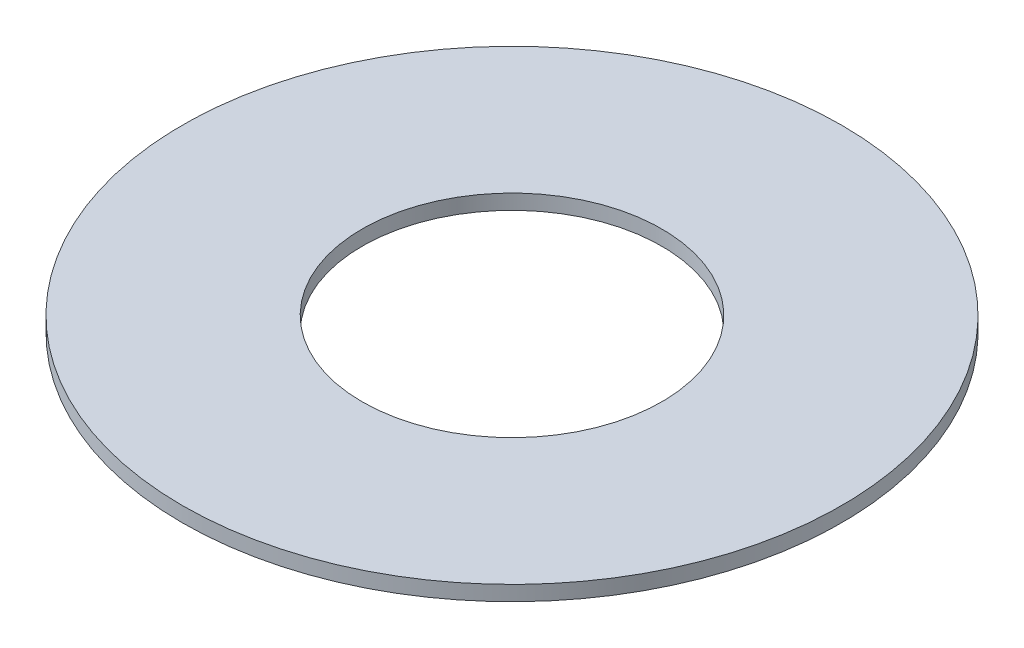
SolidWorks part; units mm, degrees
material "ПТФЭ (общий)"
ref_plane "Спереди" through (0, 0, 0) normal (0, 0, 1) x (1, 0, 0)
ref_plane "Сверху" through (0, 0, 0) normal (0, 1, 0) x (1, 0, 0)
ref_plane "Справа" through (0, 0, 0) normal (1, 0, 0) x (0, 0, -1)
sketch "Эскиз1" plane through (0, 0, 0) normal (0, 1, 0) x (1, 0, 0)
  circle A0 centre (0, 0) radius 10
  circle A1 centre (0, 0) radius 22
  dimension "Dвнутр" = 20
  dimension "Ширина" = 12
extrude "Бобышка-Вытянуть1" add sketch "Эскиз1" along normal blind 1
